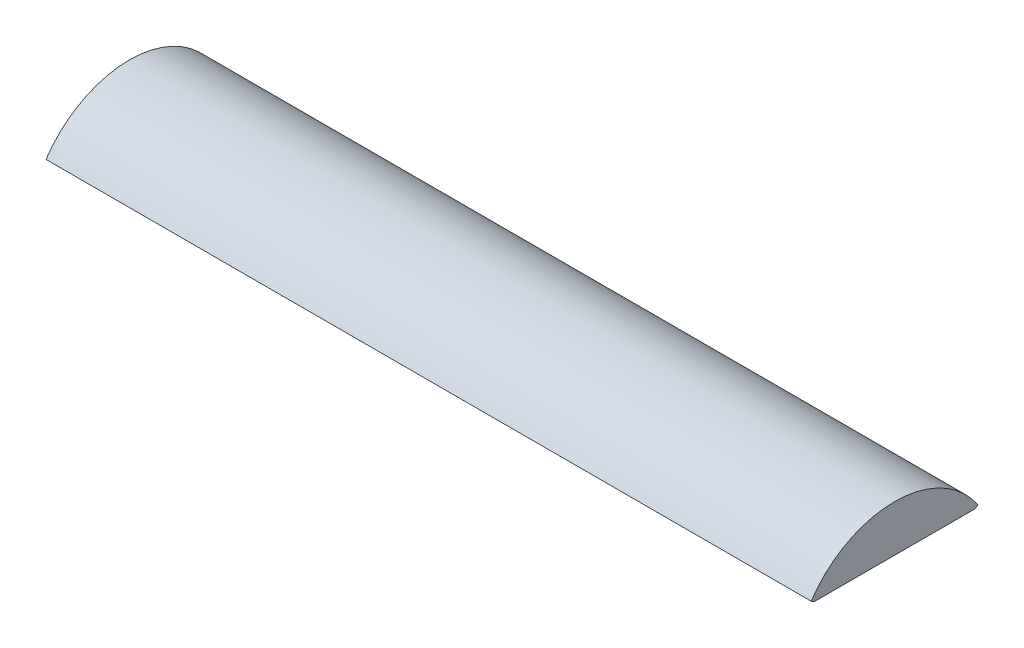
SolidWorks part; units mm, degrees
ref_plane "Alzado" through (0, 0, 0) normal (0, 0, 1) x (1, 0, 0)
ref_plane "Planta" through (0, 0, 0) normal (0, 1, 0) x (1, 0, 0)
ref_plane "Vista lateral" through (0, 0, 0) normal (1, 0, 0) x (0, 0, -1)
sketch "Croquis2" plane through (0, 0, 0) normal (1, 0, 0) x (0, 0, -1)
  line L0 (55, 0) -> (-55, 0) construction
  arc A0 (-64.1784, 0) -> (8.3216, 0) centre (-27.9284, -24.2929) cw
  dimension "D2" = 72.5
extrude "Extruir-Lámina1" add sketch "Croquis2" along normal blind 332.5 thin
sketch "Croquis3" plane through (0, 0, 0) normal (-1, 0, 0) x (0, 0, 1)
  line L0 (-7.0755, -0.8351) -> (62.9323, -0.8351)
  arc A0 (-7.0755, -0.8351) -> (62.9323, -0.8351) centre (27.9284, -24.2929) cw
extrude "Saliente-Extruir1" add sketch "Croquis3" against normal blind 0.5
sketch "Croquis4" plane through (332.5, 0, 0) normal (1, 0, 0) x (0, 0, -1)
  line L0 (-62.9323, -0.8351) -> (7.0755, -0.8351)
  arc A0 (-62.9323, -0.8351) -> (7.0755, -0.8351) centre (-27.9284, -24.2929) cw
extrude "Saliente-Extruir2" add sketch "Croquis4" against normal blind 0.5
